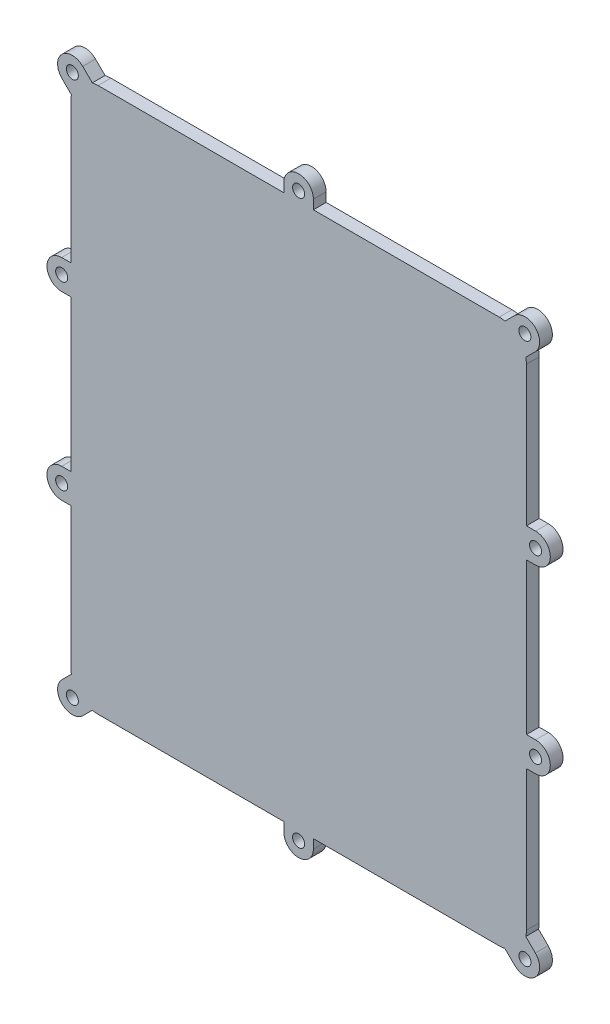
SolidWorks part; units mm, degrees
material "Acrylic (Medium-high impact)"
ref_plane "X-Y Datum" through (0, 0, 0) normal (0, 0, 1) x (1, 0, 0)
ref_plane "X-Z Datum" through (0, 0, 0) normal (0, 1, 0) x (1, 0, 0)
ref_plane "Y-Z Datum" through (0, 0, 0) normal (1, 0, 0) x (0, 0, -1)
sketch "Sketch1" plane through (0, 0, 0) normal (0, 0, 1) x (1, 0, 0)
  line L133 (139.4735, 101.6) -> (70.1335, 101.6)
  line L134 (70.1335, 101.6) -> (70.1335, 105.0097)
  line L135 (59.1335, 105.0097) -> (59.1335, 101.6)
  line L136 (59.1335, 101.6) -> (-10.2065, 101.6)
  line L137 (-12.3579, 101.3696) -> (-15.9126, 104.9243)
  line L138 (-23.6908, 97.1461) -> (-20.1361, 93.5914)
  line L139 (-20.3665, 91.44) -> (-20.3665, 39.2252)
  line L140 (-20.3665, 39.2252) -> (-23.7762, 39.2252)
  line L141 (-23.7762, 28.2252) -> (-20.3665, 28.2252)
  line L142 (-20.3665, 28.2252) -> (-20.3665, -28.2252)
  line L143 (-20.3665, -28.2252) -> (-23.7762, -28.2252)
  line L144 (-23.7762, -39.2252) -> (-20.3665, -39.2252)
  line L145 (-20.3665, -39.2252) -> (-20.3665, -91.44)
  line L146 (-20.1361, -93.5914) -> (-23.6908, -97.1461)
  line L147 (-15.9126, -104.9243) -> (-12.3579, -101.3696)
  line L148 (-10.2065, -101.6) -> (59.1335, -101.6)
  line L149 (59.1335, -101.6) -> (59.1335, -105.0097)
  line L150 (70.1335, -105.0097) -> (70.1335, -101.6)
  line L151 (70.1335, -101.6) -> (139.4735, -101.6)
  line L152 (141.625, -101.3696) -> (145.1797, -104.9243)
  line L153 (152.9578, -97.1461) -> (149.4031, -93.5914)
  line L154 (149.6335, -91.44) -> (149.6335, -39.2252)
  line L155 (149.6335, -39.2252) -> (153.0432, -39.2252)
  line L156 (153.0432, -28.2252) -> (149.6335, -28.2252)
  line L157 (149.6335, -28.2252) -> (149.6335, 28.2252)
  line L158 (149.6335, 28.2252) -> (153.0432, 28.2252)
  line L159 (153.0432, 39.2252) -> (149.6335, 39.2252)
  line L160 (149.6335, 39.2252) -> (149.6335, 91.44)
  line L161 (149.4031, 93.5914) -> (152.9578, 97.1461)
  line L162 (145.1797, 104.9243) -> (141.625, 101.3696)
  arc A90 (70.1335, 105.0097) -> (59.1335, 105.0097) centre (64.6335, 105.0097) ccw
  arc A91 (-10.2065, 101.6) -> (-12.3579, 101.3696) centre (-10.2065, 91.44) ccw
  arc A92 (-15.9126, 104.9243) -> (-23.6908, 97.1461) centre (-19.8017, 101.0352) ccw
  arc A93 (-20.1361, 93.5914) -> (-20.3665, 91.44) centre (-10.2065, 91.44) ccw
  arc A94 (-23.7762, 39.2252) -> (-23.7762, 28.2252) centre (-23.7762, 33.7252) ccw
  arc A95 (-23.7762, -28.2252) -> (-23.7762, -39.2252) centre (-23.7762, -33.7252) ccw
  arc A96 (-20.3665, -91.44) -> (-20.1361, -93.5914) centre (-10.2065, -91.44) ccw
  arc A97 (-23.6908, -97.1461) -> (-15.9126, -104.9243) centre (-19.8017, -101.0352) ccw
  arc A98 (-12.3579, -101.3696) -> (-10.2065, -101.6) centre (-10.2065, -91.44) ccw
  arc A99 (59.1335, -105.0097) -> (70.1335, -105.0097) centre (64.6335, -105.0097) ccw
  arc A100 (139.4735, -101.6) -> (141.625, -101.3696) centre (139.4735, -91.44) ccw
  arc A101 (145.1797, -104.9243) -> (152.9578, -97.1461) centre (149.0688, -101.0352) ccw
  arc A102 (149.4031, -93.5914) -> (149.6335, -91.44) centre (139.4735, -91.44) ccw
  arc A103 (153.0432, -39.2252) -> (153.0432, -28.2252) centre (153.0432, -33.7252) ccw
  arc A104 (153.0432, 28.2252) -> (153.0432, 39.2252) centre (153.0432, 33.7252) ccw
  arc A105 (149.6335, 91.44) -> (149.4031, 93.5914) centre (139.4735, 91.44) ccw
  arc A106 (152.9578, 97.1461) -> (145.1797, 104.9243) centre (149.0688, 101.0352) ccw
  arc A107 (141.625, 101.3696) -> (139.4735, 101.6) centre (139.4735, 91.44) ccw
extrude "Boss-Extrude1" add sketch "Sketch1" along normal blind 4.7625
hole_wizard "M4 Clearance Hole1" positions "Sketch2" profile "Sketch3" hole size "M4" standard "ANSI Metric" end condition through all
sketch "Sketch2" plane through (0, 0, 4.7625) normal (0, 0, 1) x (1, 0, 0)
  point P0 (-19.8017, -101.0352)
  point P2 (-23.7762, -33.7252)
  point P4 (-23.7762, 33.7252)
  point P6 (-19.8017, 101.0352)
  point P8 (64.6335, 105.0097)
  point P10 (149.0688, 101.0352)
  point P12 (153.0432, 33.7252)
  point P14 (153.0432, -33.7252)
  point P16 (149.0688, -101.0352)
  point P18 (64.6335, -105.0097)
sketch "Sketch3" plane through (-19.8017, -101.0352, 4.7625) normal (1, 0, 0) x (0, -1, 0)
  line L0 (0, 0) -> (0, 4.7625)
  line L1 (0, 4.7625) -> (2.25, 4.7625)
  line L2 (2.25, 4.7625) -> (2.25, 0)
  line L5 (2.25, 0) -> (0, 0)
  line L11 (0, -6.35) -> (0, 107.95) construction
  dimension "Thru Hole Dia." = 4.5
  dimension "Thru Hole Depth" = 4.7625
